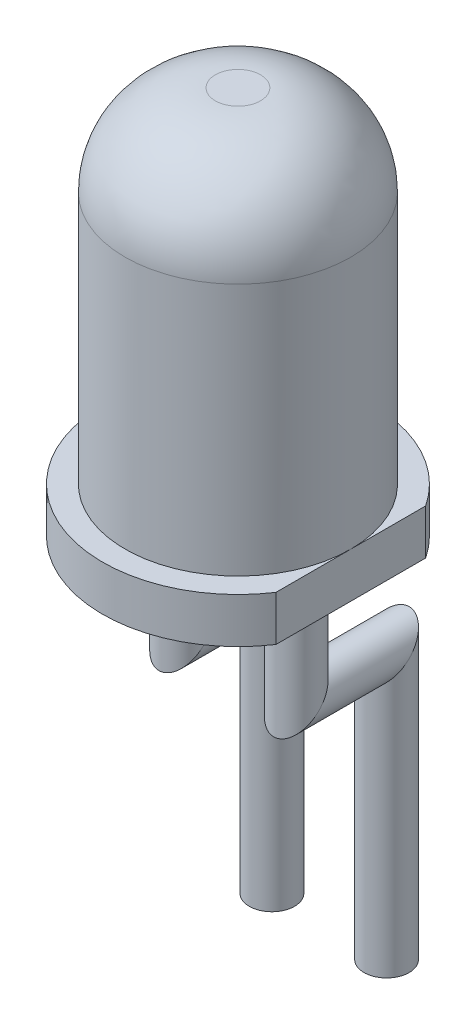
SolidWorks part; units mm, degrees
ref_plane "Piano frontale" through (0, 0, 0) normal (0, 0, 1) x (1, 0, 0)
ref_plane "Piano superiore" through (0, 0, 0) normal (0, 1, 0) x (1, 0, 0)
ref_plane "Piano destro" through (0, 0, 0) normal (1, 0, 0) x (0, 0, -1)
sketch "Schizzo1" plane through (0, 0, 0) normal (0, 1, 0) x (1, 0, 0)
  circle A0 centre (0, 0) radius 3
  dimension "D1" = 6
extrude "Estrusione-Estrusione1" add sketch "Schizzo1" along normal blind 1
sketch "Schizzo2" plane through (0, 1, 0) normal (0, 1, 0) x (1, 0, 0)
  circle A0 centre (0, 0) radius 2.5
  dimension "D1" = 5
extrude "Estrusione-Estrusione2" add sketch "Schizzo2" along normal blind 7.6
fillet "Raccordo3" radius 2 1 edges at (0, 8.6, 2.5)
ref_plane "Piano1" through (1.27, 0, 0) normal (1, 0, 0) x (0, 0, -1)
sketch "Schizzo5" plane through (1.27, 0, 0) normal (1, 0, 0) x (0, 0, -1)
  line L0 (0, 0) -> (0, -2.5)
  line L1 (-3, 0) -> (3, 0) construction
  line L2 (0, -2.5) -> (2, -2.5)
  line L3 (2, -2.5) -> (2, -8.5)
  dimension "D1" = 2.5
  dimension "D2" = 2
  dimension "D3" = 6
sketch "Schizzo6" plane through (0, 0, 0) normal (0, -1, 0) x (1, 0, 0)
  line L1 (1.27, -3.3) -> (1.27, 3.3) construction
  circle A0 centre (1.27, -0.0224) radius 0.5
  dimension "D1" = 1
sweep "Sweep1" add profiles "Schizzo6" path "Schizzo5"
mirror "Specchia1" about plane through (0, 0, 0) normal (1, 0, 0) of "Sweep1"
ref_plane "Piano2" through (2.5, 0, 0) normal (1, 0, 0) x (0, 0, -1)
sketch "Schizzo7" plane through (2.5, 0, 0) normal (1, 0, 0) x (0, 0, -1)
  line L0 (2.5, 1) -> (2.5, 6.6) construction
  line L1 (-2.4515, -1.6508) -> (2.5, -1.6508)
  line L2 (-2.4515, -1.6508) -> (-2.4515, 2.9473)
  line L3 (-2.4515, 2.9473) -> (2.5, 2.9473)
  line L4 (2.5, -1.6508) -> (2.5, 2.9473)
  line L5 (-2.4515, -1.6508) -> (2.5, 2.9473) construction
  line L6 (-2.4515, 2.9473) -> (2.5, -1.6508) construction
  point P0 (0.0242, 0.6482)
  point P5 (0, 0)
  point P6 (2.5, 2.9473)
extrude "Taglio-Estrusione1" cut sketch "Schizzo7" along normal blind 10
